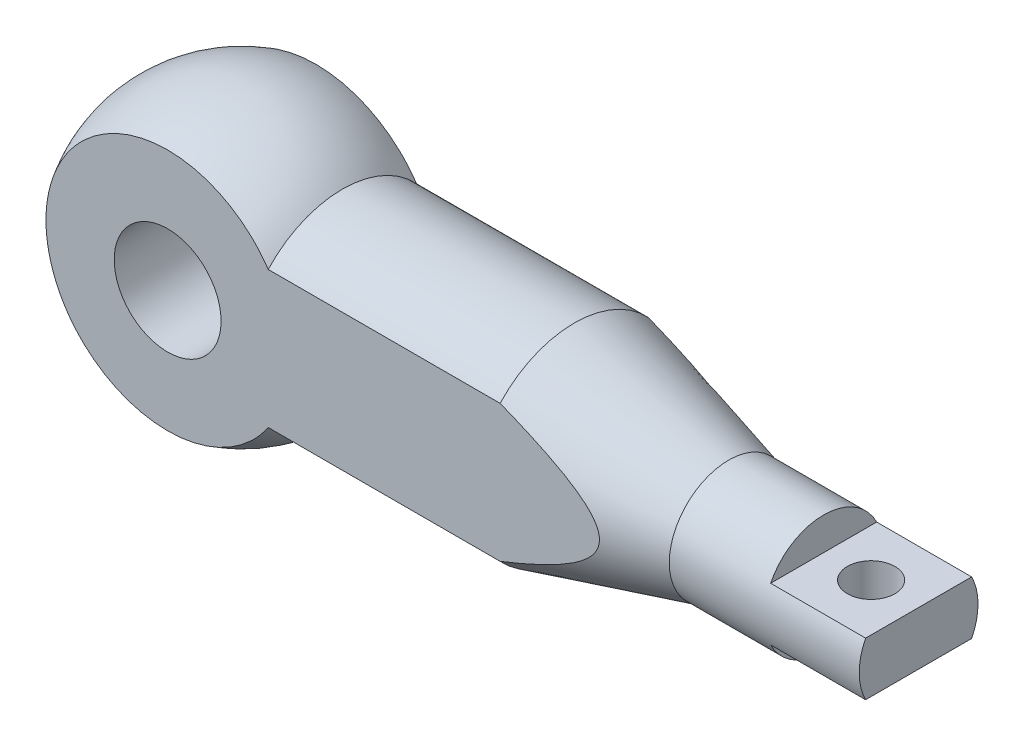
SolidWorks part; units mm, degrees
ref_plane "Alzado" through (0, 0, 0) normal (0, 0, 1) x (1, 0, 0)
ref_plane "Planta" through (0, 0, 0) normal (0, 1, 0) x (1, 0, 0)
ref_plane "Vista lateral" through (0, 0, 0) normal (1, 0, 0) x (0, 0, -1)
sketch "Croquis2" plane through (0, 0, 0) normal (0, 0, 1) x (1, 0, 0)
  line L0 (-38.1, 0) -> (180.975, 0)
  line L1 (26.894, 26.9875) -> (88.9, 26.9875)
  line L2 (180.975, 0) -> (180.975, 15.875)
  line L3 (180.975, 15.875) -> (130.175, 15.875)
  line L4 (88.9, 26.9875) -> (130.175, 15.875)
  arc A0 (-38.1, 0) -> (26.894, 26.9875) centre (0, 0) cw
  dimension "D1" = 38.1
  dimension "D2" = 219.075
  dimension "D3" = 26.9875
  dimension "D4" = 15.875
  dimension "D5" = 50.8
  dimension "D6" = 41.275
revolve "Revolución1" add sketch "Croquis2" angle 360 about L0
sketch "Croquis3" plane through (180.975, 0, 0) normal (1, 0, 0) x (0, 0, -1)
  line L0 (-19.8374, 32.5283) -> (-19.8374, -32.5283)
  line L1 (19.8374, 32.5283) -> (19.8374, -32.5283)
  arc A2 (-19.8374, 32.5283) -> (-19.8374, -32.5283) centre (0, 0) ccw
  arc A3 (19.8374, -32.5283) -> (19.8374, 32.5283) centre (0, 0) ccw
  dimension "D1" = 39.6748
  dimension "D2" = 19.8374
extrude "Cortar-Extruir1" cut sketch "Croquis3" against normal through all and the other way through all
sketch "Croquis4" plane through (180.975, 0, 0) normal (1, 0, 0) x (0, 0, -1)
  line L0 (-14.18, 7.1374) -> (14.18, 7.1374)
  line L1 (-14.18, -7.1374) -> (14.18, -7.1374)
  arc A0 (-14.18, -7.1374) -> (14.18, -7.1374) centre (0, 0) ccw
  arc A1 (14.18, 7.1374) -> (-14.18, 7.1374) centre (0, 0) ccw
  dimension "D1" = 14.2748
  dimension "D2" = 7.1374
extrude "Cortar-Extruir2" cut sketch "Croquis4" against normal blind 25.4
sketch "Croquis5" plane through (0, 7.1374, 0) normal (0, 1, 0) x (1, 0, 0)
  line L0 (155.575, -14.18) -> (155.575, 14.18) construction
  circle A0 centre (168.275, 0) radius 6.35
  dimension "D2" = 12.7
  dimension "D1" = 12.7
extrude "Cortar-Extruir3" cut sketch "Croquis5" against normal up to next
sketch "Croquis6" plane through (0, 0, 19.8374) normal (0, 0, 1) x (1, 0, 0)
  circle A0 centre (0, 0) radius 14.2875
  dimension "D1" = 28.575
extrude "Cortar-Extruir4" cut sketch "Croquis6" against normal up to next
